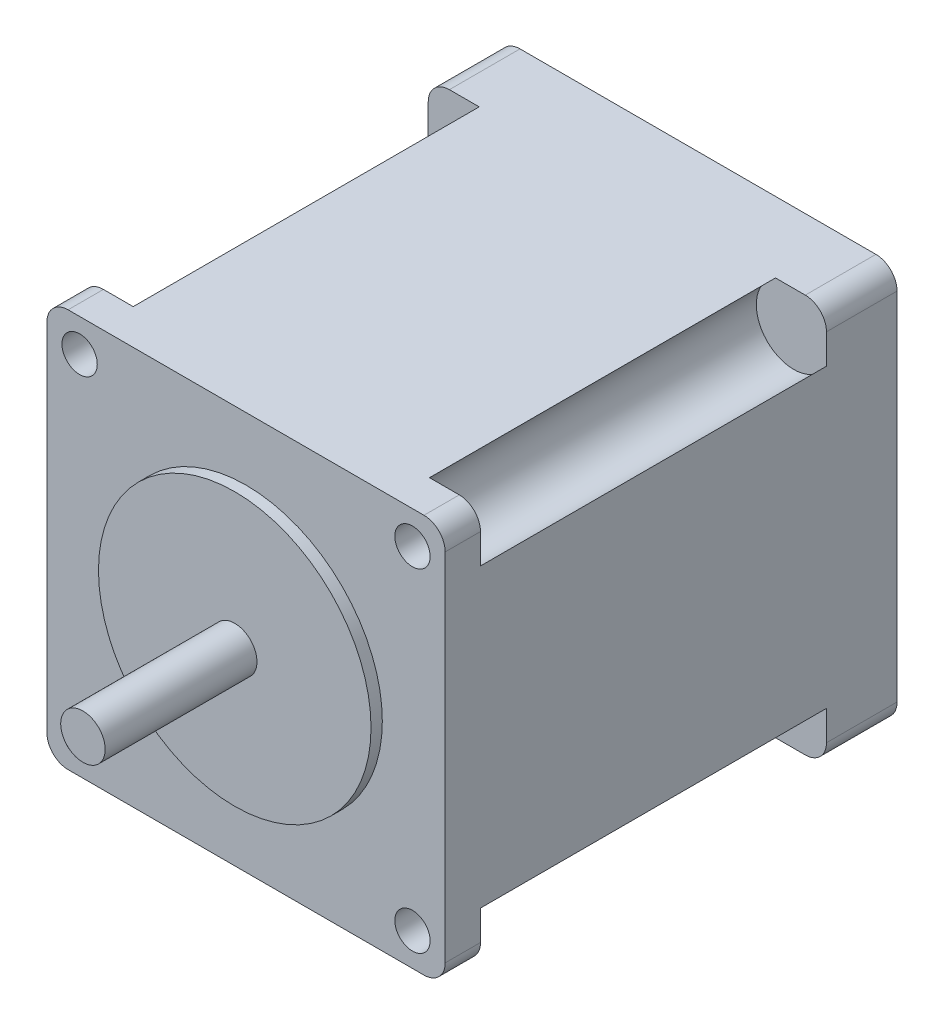
SolidWorks part; units mm, degrees
material "AISI 304"
ref_plane "Front Plane" through (0, 0, 0) normal (0, 0, 1) x (1, 0, 0)
ref_plane "Top Plane" through (0, 0, 0) normal (0, 1, 0) x (1, 0, 0)
ref_plane "Right Plane" through (0, 0, 0) normal (1, 0, 0) x (0, 0, -1)
sketch "Sketch1" plane through (0, 0, 0) normal (0, 0, 1) x (1, 0, 0)
  line L1 (0, 0) -> (56.4, 0)
  line L2 (0, 0) -> (0, 56.4)
  line L3 (0, 56.4) -> (56.4, 56.4)
  line L4 (56.4, 0) -> (56.4, 56.4)
  dimension "D1" = 56.4
  dimension "D2" = 56.4
extrude "Extrude1" add sketch "Sketch1" along normal blind 64
sketch "Sketch2" plane through (0, 0, 64) normal (0, 0, 1) x (1, 0, 0)
  line L0 (0, 0) -> (56.4, 0) construction
  line L1 (0, 56.4) -> (0, 0) construction
  circle A0 centre (28.2, 28.2) radius 19.3
  point P2 (28.2, 0)
  dimension "D1" = 38.6
  dimension "D2" = 28.2
  dimension "D3" = 28.2
extrude "Extrude2" add sketch "Sketch2" along normal blind 1.6 separate body
sketch "Sketch3" plane through (0, 0, 65.6) normal (0, 0, 1) x (1, 0, 0)
  circle A0 centre (28.2, 28.2) radius 3.15
  circle A1 centre (28.2, 28.2) radius 19.3 construction
  dimension "D1" = 6.3
extrude "Extrude3" add sketch "Sketch3" along normal blind 21.5
fillet "Fillet1" radius 3 4 edges at (0, 0, 32) (56.4, 0, 32) (56.4, 56.4, 32) (0, 56.4, 32)
sketch "Sketch4" plane through (0, 0, 64) normal (0, 0, 1) x (1, 0, 0)
  line L0 (4.63, 51.77) -> (51.77, 51.77) construction
  line L1 (51.77, 51.77) -> (51.77, 4.63) construction
  line L2 (51.77, 4.63) -> (4.63, 4.63) construction
  line L3 (4.63, 4.63) -> (4.63, 51.77) construction
  line L4 (28.2, 51.77) -> (28.2, 28.2) construction
  circle A0 centre (28.2, 28.2) radius 3.15 construction
  circle A1 centre (4.63, 51.77) radius 2.5
  circle A2 centre (51.77, 51.77) radius 2.5
  circle A3 centre (51.77, 4.63) radius 2.5
  circle A4 centre (4.63, 4.63) radius 2.5
  dimension "D3" = 5
  dimension "D1" = 47.14
  dimension "D2" = 23.57
extrude "Cut-Extrude1" cut sketch "Sketch4" against normal blind 6
ref_plane "Plane1" through (0, 0, 59) normal (0, 0, 1) x (1, 0, 0)
sketch "Sketch6" plane through (0, 0, 59) normal (0, 0, 1) x (1, 0, 0)
  circle A0 centre (4.63, 51.77) radius 5.3052
  circle A1 centre (51.77, 51.77) radius 5.3052
  circle A2 centre (4.63, 4.63) radius 5.3052
  circle A3 centre (51.77, 4.63) radius 5.3052
  arc A4 (3, 56.4) -> (0, 53.4) centre (3, 53.4) ccw construction
extrude "Cut-Extrude2" cut sketch "Sketch6" against normal blind 49
